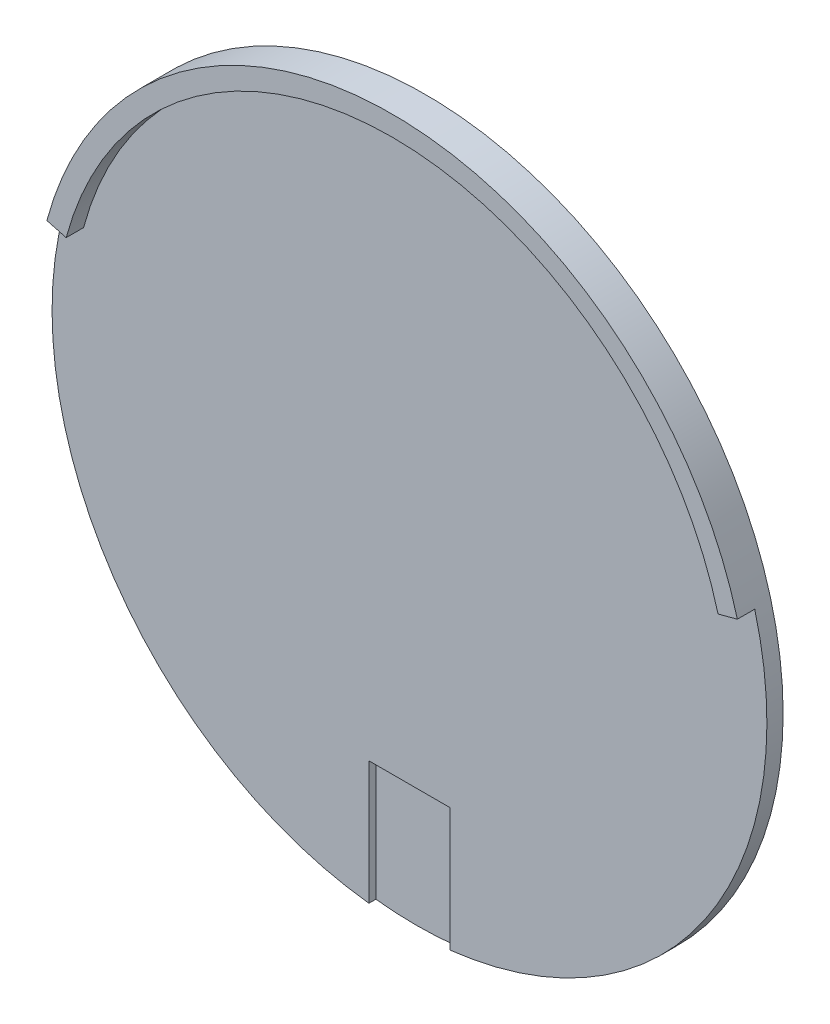
SolidWorks part; units mm, degrees
ref_plane "Front Plane" through (0, 0, 0) normal (0, 0, 1) x (1, 0, 0)
ref_plane "Top Plane" through (0, 0, 0) normal (0, 1, 0) x (1, 0, 0)
ref_plane "Right Plane" through (0, 0, 0) normal (1, 0, 0) x (0, 0, -1)
ref_plane "Plane_Z+72.00" through (0, 0, 72) normal (0, 0, 1) x (1, 0, 0)
sketch "Sketch1" plane through (0, 0, 72) normal (0, 0, 1) x (1, 0, 0)
  circle A0 centre (70, 0) radius 61.7
extrude "Seat_disc" add sketch "Sketch1" along normal blind 2.8
ref_plane "Plane_Z+74.80" through (0, 0, 74.8) normal (0, 0, 1) x (1, 0, 0)
sketch "Sketch2" plane through (0, 0, 74.8) normal (0, 0, 1) x (1, 0, 0)
  line L0 (126.2652, 15.0762) -> (129.5976, 15.9691)
  line L1 (10.4024, 15.9691) -> (13.7348, 15.0762)
  arc A0 (129.5976, 15.9691) -> (10.4024, 15.9691) centre (70, 0) ccw
  arc A1 (13.7348, 15.0762) -> (126.2652, 15.0762) centre (70, 0) cw
extrude "Rear_stop_arc" add sketch "Sketch2" along normal blind 3
ref_plane "Plane_Z+74.45" through (0, 0, 74.45) normal (0, 0, 1) x (1, 0, 0)
sketch "Sketch3" plane through (0, 0, 74.45) normal (0, 0, 1) x (1, 0, 0)
  line L0 (63, -63) -> (77, -63)
  line L1 (77, -63) -> (77, -40)
  line L2 (77, -40) -> (63, -40)
  line L3 (63, -40) -> (63, -63)
extrude "Front_drain_groove" cut sketch "Sketch3" against normal mid plane 1.7
ref_plane "Plane_Z+72.75" through (0, 0, 72.75) normal (0, 0, 1) x (1, 0, 0)
sketch "Sketch4" plane through (0, 0, 72.75) normal (0, 0, 1) x (1, 0, 0)
  circle A0 centre (70, 50) radius 1
  circle A1 centre (26.6987, -25) radius 1
  circle A2 centre (113.3013, -25) radius 1
extrude "Pin_holes" cut sketch "Sketch4" against normal mid plane 2.5
